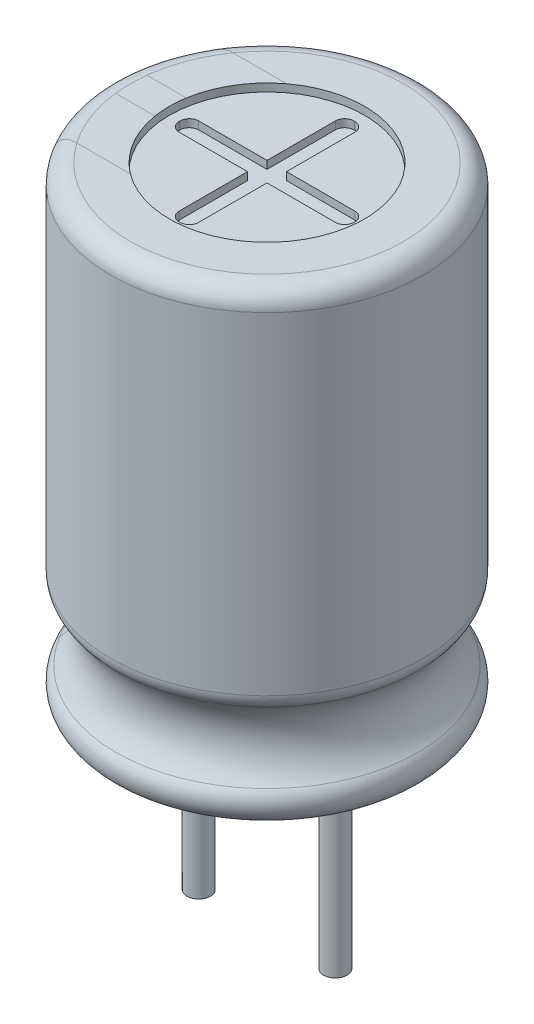
SolidWorks part; units mm, degrees
ref_plane "Front" through (0, 0, 0) normal (0, 0, 1) x (1, 0, 0)
ref_plane "Top" through (0, 0, 0) normal (0, 1, 0) x (1, 0, 0)
ref_plane "Right" through (0, 0, 0) normal (1, 0, 0) x (0, 0, -1)
sketch "Эскиз2" plane through (0, 0, 0) normal (0, 0, 1) x (1, 0, 0)
  line L0 (0, 0) -> (3.5, 0)
  line L1 (4, 3) -> (4, 11.5)
  line L2 (3.5, 12) -> (0, 12)
  line L3 (0, 0) -> (0, 12) construction
  line L4 (0, 0) -> (0, 12)
  arc A0 (3.5, 0) -> (4, 0.5) centre (3.5, 0.5) ccw
  arc A1 (4, 11.5) -> (3.5, 12) centre (3.5, 11.5) ccw
  arc A2 (4, 0.5) -> (3.8621, 0.8448) centre (3.5, 0.5) ccw
  arc A3 (3.8621, 2.6552) -> (3.8621, 0.8448) centre (4.8125, 1.75) ccw
  arc A4 (3.8621, 2.6552) -> (4, 3) centre (3.5, 3) ccw
  point P7 (4, 0)
  point P10 (4, 12)
  point P31 (3.5, 1.75)
  dimension "D3" = 0.5
  dimension "D4" = 0.5
  dimension "D1" = 4
  dimension "D2" = 12
  dimension "D5" = 2.5
revolve "Повернуть1" add sketch "Эскиз2" angle 360 about L3
sketch "Эскиз3" plane through (0, 12, 0) normal (0, 1, 0) x (1, 0, 0)
  circle A0 centre (0, 0) radius 2.5
  dimension "D1" = 5
extrude "Вырез-Вытянуть1" cut sketch "Эскиз3" against normal blind 0.2
sketch "Эскиз4" plane through (0, 11.8, 0) normal (0, 1, 0) x (1, 0, 0)
  line L0 (-0.25, -0.25) -> (-0.25, -2)
  line L1 (-0.01, 2.24) -> (0.01, 2.24)
  line L2 (-0.25, 2) -> (-0.25, 0.25)
  line L3 (-0.01, -2.24) -> (0.01, -2.24)
  line L4 (0.25, 2) -> (0.25, 0.25)
  line L5 (-2, 0.25) -> (-0.25, 0.25)
  line L6 (-2.24, 0.01) -> (-2.24, -0.01)
  line L7 (-2, -0.25) -> (-0.25, -0.25)
  line L8 (2.24, 0.01) -> (2.24, -0.01)
  line L9 (0.25, 0.25) -> (2, 0.25)
  line L10 (0.25, -0.25) -> (0.25, -2)
  line L11 (0.25, -0.25) -> (2, -0.25)
  arc A0 (0.01, 2.24) -> (0.25, 2) centre (0.01, 2) cw
  arc A1 (-0.01, 2.24) -> (-0.25, 2) centre (-0.01, 2) ccw
  arc A2 (2, -0.25) -> (2.24, -0.01) centre (2, -0.01) ccw
  arc A3 (2, 0.25) -> (2.24, 0.01) centre (2, 0.01) cw
  arc A4 (0.01, -2.24) -> (0.25, -2) centre (0.01, -2) ccw
  arc A5 (-0.25, -2) -> (-0.01, -2.24) centre (-0.01, -2) ccw
  arc A6 (-2.24, -0.01) -> (-2, -0.25) centre (-2, -0.01) ccw
  arc A7 (-2, 0.25) -> (-2.24, 0.01) centre (-2, 0.01) ccw
  circle A8 centre (0, 0) radius 2.5 construction
  point P15 (0.25, 2.24)
  point P18 (-0.25, 2.24)
  point P23 (2.24, 0.25)
  point P26 (0.25, -2.24)
  point P31 (-2.24, -0.25)
  point P34 (-2.24, 0.25)
  point P35 (-2.2371, 0)
  point P36 (-0.25, 1.8268)
  dimension "D9" = 0.24
  dimension "D5" = 2
  dimension "D1" = 0.5
  dimension "D2" = 0.5
  dimension "D3" = 0.25
  dimension "D4" = 0.25
extrude "Вырез-Вытянуть2" cut sketch "Эскиз4" against normal blind 0.2
sketch "Эскиз5" plane through (0, 0, 0) normal (0, -1, 0) x (1, 0, 0)
  circle A0 centre (0, 0) radius 2.5
  dimension "D1" = 5
extrude "Вырез-Вытянуть3" cut sketch "Эскиз5" against normal blind 0.2
sketch "Эскиз6" plane through (0, 0.2, 0) normal (0, -1, 0) x (1, 0, 0)
  line L1 (-5.3376, 2) -> (5.3376, 2)
  line L3 (-5.3376, -2) -> (5.3376, -2)
  arc A0 (-5.3376, -2) -> (5.3376, -2) centre (0, 0) ccw
  arc A1 (5.3376, 2) -> (-5.3376, 2) centre (0, 0) ccw
  dimension "D1" = 11.4
  dimension "D2" = 4
  dimension "D3" = 2
extrude "Бобышка-Вытянуть1" [suppressed] add sketch "Эскиз6" along normal blind 1.2
sketch "Эскиз7" plane through (0, 0.2, 0) normal (0, -1, 0) x (1, 0, 0)
  circle A0 centre (-1.75, 0) radius 0.3
  circle A1 centre (1.75, 0) radius 0.3
  dimension "D2" = 0.6
  dimension "D3" = 3.5
  dimension "D4" = 1.75
extrude "Бобышка-Вытянуть2" add sketch "Эскиз7" along normal blind 5.2
ref_plane "Плоскость1" through (4, 0, 0) normal (1, 0, 0) x (0, 0, -1)
sketch "Эскиз9" plane through (0, 0, 0) normal (1, 0, 0) x (0, 0, -1)
  line L0 (-0.3, -5) -> (0.3, -5) construction
  line L1 (-2, 35) -> (2, 35)
  line L2 (-2, 35) -> (-2, -5)
  line L3 (-2, -5) -> (2, -5)
  line L4 (2, 35) -> (2, -5)
  line L5 (-0.4, 30) -> (-0.4, 28)
  line L6 (-0.4, 34) -> (0.4, 34)
  line L7 (-0.4, 34) -> (-0.4, 32)
  line L8 (-0.4, 32) -> (0.4, 32)
  line L9 (0.4, 34) -> (0.4, 32)
  line L10 (-0.4, 30) -> (0.4, 30)
  line L11 (0.4, 30) -> (0.4, 28)
  line L12 (-0.4, 28) -> (0.4, 28)
  line L13 (-0.4, 26) -> (-0.4, 24)
  line L14 (-0.4, 26) -> (0.4, 26)
  line L15 (0.4, 26) -> (0.4, 24)
  line L16 (-0.4, 24) -> (0.4, 24)
  line L17 (-0.4, 22) -> (-0.4, 20)
  line L18 (-0.4, 22) -> (0.4, 22)
  line L19 (0.4, 22) -> (0.4, 20)
  line L20 (-0.4, 20) -> (0.4, 20)
  line L21 (-0.4, 18) -> (-0.4, 16)
  line L22 (-0.4, 18) -> (0.4, 18)
  line L23 (0.4, 18) -> (0.4, 16)
  line L24 (-0.4, 16) -> (0.4, 16)
  line L25 (-0.4, 14) -> (-0.4, 12)
  line L26 (-0.4, 14) -> (0.4, 14)
  line L27 (0.4, 14) -> (0.4, 12)
  line L28 (-0.4, 12) -> (0.4, 12)
  line L29 (-0.4, 10) -> (-0.4, 8)
  line L30 (-0.4, 10) -> (0.4, 10)
  line L31 (0.4, 10) -> (0.4, 8)
  line L32 (-0.4, 8) -> (0.4, 8)
  line L33 (-0.4, 6) -> (-0.4, 4)
  line L34 (-0.4, 6) -> (0.4, 6)
  line L35 (0.4, 6) -> (0.4, 4)
  line L36 (-0.4, 4) -> (0.4, 4)
  line L37 (-0.4, 2) -> (-0.4, 0)
  line L38 (-0.4, 2) -> (0.4, 2)
  line L39 (0.4, 2) -> (0.4, 0)
  line L40 (-0.4, 0) -> (0.4, 0)
  line L41 (-0.4, -2) -> (-0.4, -4)
  line L42 (-0.4, -2) -> (0.4, -2)
  line L43 (0.4, -2) -> (0.4, -4)
  line L44 (-0.4, -4) -> (0.4, -4)
  point P11 (0, 34)
  point P12 (0, 35)
  dimension "D1" = 4
  dimension "D2" = 2
  dimension "D3" = 40
  dimension "D4" = 2
  dimension "D5" = 0.8
  dimension "D6" = 1
  dimension "D8" = 4
  dimension "D7" = 10
split line "Разделяющая линия5"
